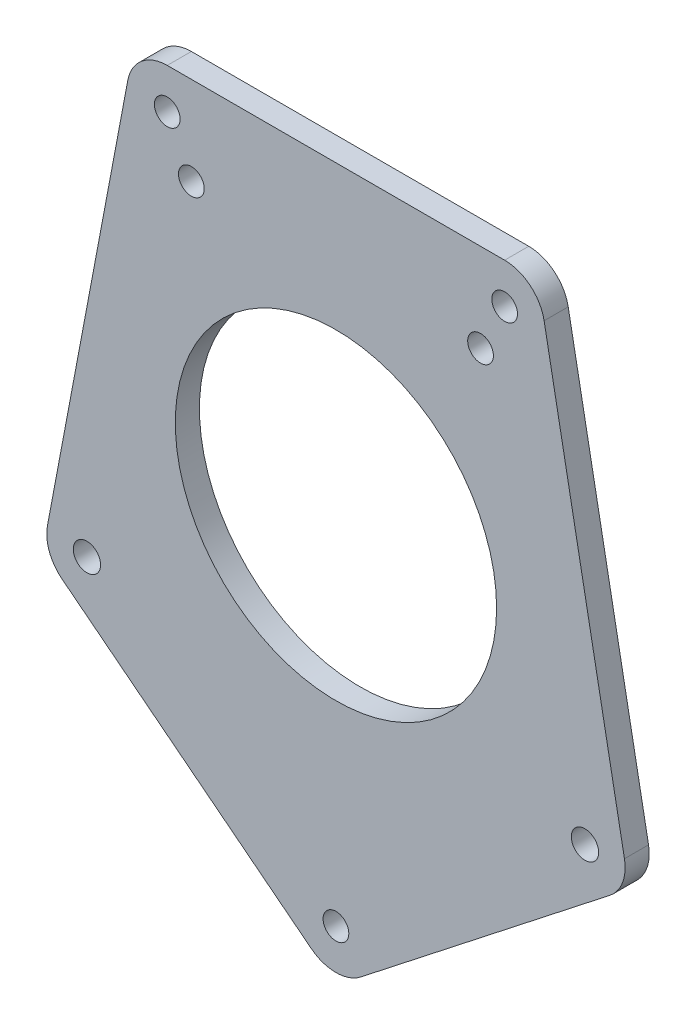
SolidWorks part; units mm, degrees
ref_plane "前视基准面" through (0, 0, 0) normal (0, 0, 1) x (1, 0, 0)
ref_plane "上视基准面" through (0, 0, 0) normal (0, 1, 0) x (1, 0, 0)
ref_plane "右视基准面" through (0, 0, 0) normal (1, 0, 0) x (0, 0, -1)
sketch "草图1" plane through (0, 0, 0) normal (0, 0, 1) x (1, 0, 0)
  line L5 (21, 58) -> (-21, 58)
  line L6 (-25.9133, 53.927) -> (-35.9133, 0.927)
  line L7 (-34.0846, -3.9351) -> (-3.0846, -28.2351)
  line L8 (3.0846, -28.2351) -> (34.0846, -3.9351)
  line L9 (35.9133, 0.927) -> (25.9133, 53.927)
  circle A0 centre (21, 53) radius 1.6
  circle A1 centre (-21, 53) radius 1.6
  circle A2 centre (31, 0) radius 1.7
  circle A3 centre (-31, 0) radius 1.7
  circle A4 centre (18, 47) radius 1.6
  circle A5 centre (-18, 47) radius 1.6
  circle A6 centre (0, -24.3) radius 1.6
  arc A7 (-35.9133, 0.927) -> (-34.0846, -3.9351) centre (-31, 0) ccw
  arc A8 (-3.0846, -28.2351) -> (3.0846, -28.2351) centre (0, -24.3) ccw
  arc A9 (34.0846, -3.9351) -> (35.9133, 0.927) centre (31, 0) ccw
  arc A10 (25.9133, 53.927) -> (21, 58) centre (21, 53) ccw
  arc A11 (-21, 58) -> (-25.9133, 53.927) centre (-21, 53) ccw
  circle A12 centre (0, 20) radius 20
  dimension "D1" = 5
extrude "凸台-拉伸1" add sketch "草图1" along normal blind 3
